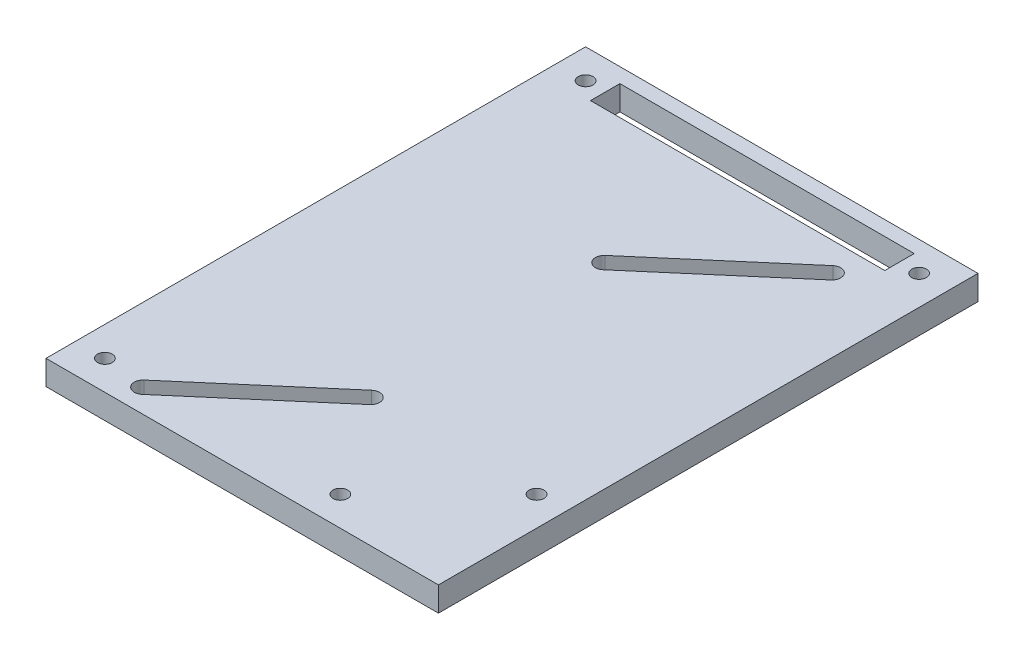
SolidWorks part; units mm, degrees
ref_plane "Front Plane" through (0, 0, 0) normal (0, 0, 1) x (1, 0, 0)
ref_plane "Top Plane" through (0, 0, 0) normal (0, 1, 0) x (1, 0, 0)
ref_plane "Right Plane" through (0, 0, 0) normal (1, 0, 0) x (0, 0, -1)
sketch "Sketch1" plane through (0, 0, 0) normal (0, 1, 0) x (1, 0, 0)
  line L1 (-50.8, -63.5) -> (50.8, -63.5)
  line L2 (-50.8, -63.5) -> (-50.8, 76.2)
  line L3 (-50.8, 76.2) -> (50.8, 76.2)
  line L4 (50.8, -63.5) -> (50.8, 76.2)
  dimension "D1" = 101.6
  dimension "D2" = 139.7
  dimension "D3" = 50.8
  dimension "D4" = 63.5
extrude "Boss-Extrude1" add sketch "Sketch1" along normal blind 6.35
sketch "Sketch3" plane through (0, 6.35, 0) normal (0, 1, 0) x (1, 0, 0)
  line L0 (0, -63.5) -> (0, 76.2) construction
  line L1 (-50.8, -63.5) -> (50.8, -63.5) construction
  line L2 (50.8, 76.2) -> (-50.8, 76.2) construction
  line L3 (0, 30.226) -> (31.75, 57.404) construction
  line L4 (50.8, -63.5) -> (50.8, 76.2) construction
  line L5 (50.8, 0) -> (-50.8, 0) construction
  line L6 (-50.8, 76.2) -> (-50.8, -63.5) construction
  line L7 (-1.4866, 31.9626) -> (30.2634, 59.1406)
  line L8 (1.4866, 28.4894) -> (33.2366, 55.6674)
  line L9 (0, -30.226) -> (-31.75, -57.404) construction
  line L10 (1.4866, -31.9626) -> (-30.2634, -59.1406)
  line L11 (-1.4866, -28.4894) -> (-33.2366, -55.6674)
  arc A0 (-1.4866, 31.9626) -> (1.4866, 28.4894) centre (0, 30.226) ccw
  arc A1 (33.2366, 55.6674) -> (30.2634, 59.1406) centre (31.75, 57.404) ccw
  arc A2 (1.4866, -31.9626) -> (-1.4866, -28.4894) centre (0, -30.226) ccw
  arc A3 (-33.2366, -55.6674) -> (-30.2634, -59.1406) centre (-31.75, -57.404) ccw
  point P15 (15.875, 43.815)
  point P24 (-15.875, -43.815)
  point P29 (0, 0)
  dimension "D1" = 30.226
  dimension "D2" = 27.178
  dimension "D3" = 31.75
  dimension "D4" = 4.572
  dimension "D5" = 2
extrude "Cut-Extrude1" cut sketch "Sketch3" against normal through all
sketch "Sketch4" plane through (0, 6.35, 0) normal (0, 1, 0) x (1, 0, 0)
  line L0 (0, 76.2) -> (0, -63.5) construction
  line L1 (50.8, 76.2) -> (-50.8, 76.2) construction
  line L2 (-50.8, -63.5) -> (50.8, -63.5) construction
  line L4 (-38.1, 64.77) -> (38.1, 64.77)
  line L5 (-38.1, 64.77) -> (-38.1, 72.39)
  line L6 (-38.1, 72.39) -> (38.1, 72.39)
  line L7 (38.1, 64.77) -> (38.1, 72.39)
  line L8 (-38.1, 64.77) -> (38.1, 72.39) construction
  line L9 (-38.1, 72.39) -> (38.1, 64.77) construction
  point P6 (0, 68.58)
  dimension "D1" = 7.62
  dimension "D2" = 7.62
  dimension "D3" = 76.2
extrude "Cut-Extrude2" cut sketch "Sketch4" against normal through all
sketch "Sketch7" plane through (0, 6.35, 0) normal (0, 1, 0) x (1, 0, 0)
  line L0 (50.8, 76.2) -> (-50.8, 76.2) construction
  line L1 (-50.8, 76.2) -> (-50.8, -63.5) construction
  line L2 (0, 76.2) -> (0, -63.5) construction
  line L3 (-50.8, -63.5) -> (50.8, -63.5) construction
  line L4 (50.8, -63.5) -> (0, -12.7) construction
  line L5 (50.8, -63.5) -> (50.8, 76.2) construction
  circle A0 centre (-43.18, 68.58) radius 1.905
  circle A1 centre (43.18, 68.58) radius 1.905
  circle A2 centre (-43.18, -55.88) radius 1.905
  circle A3 centre (17.78, -55.88) radius 1.905
  circle A4 centre (43.18, -30.48) radius 1.905
  dimension "D1" = 3.81
  dimension "D4" = 3.81
  dimension "D8" = 3.81
  dimension "D2" = 7.62
  dimension "D3" = 7.62
  dimension "D5" = 7.62
  dimension "D6" = 7.62
  dimension "D7" = 50.8
  dimension "D9" = 7.62
  dimension "D10" = 33.02
extrude "Cut-Extrude3" cut sketch "Sketch7" against normal through all
